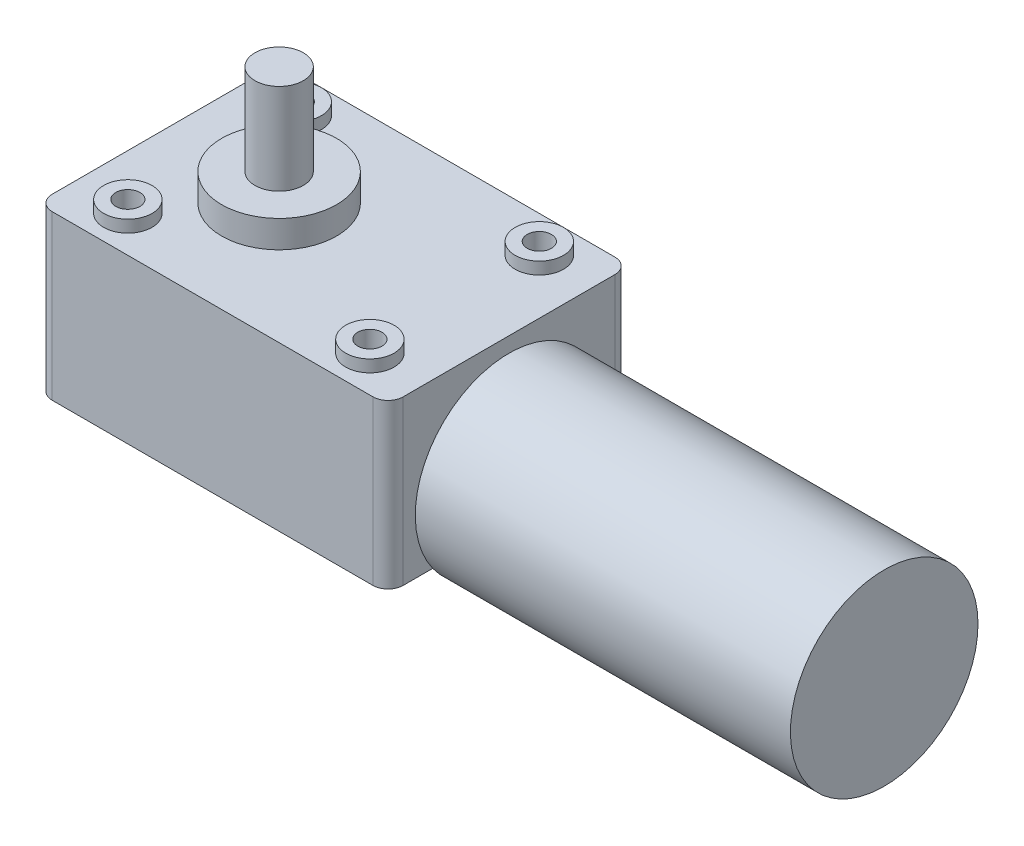
SolidWorks part; units mm, degrees
ref_plane "Front Plane" through (0, 0, 0) normal (0, 0, 1) x (1, 0, 0)
ref_plane "Top Plane" through (0, 0, 0) normal (0, 1, 0) x (1, 0, 0)
ref_plane "Right Plane" through (0, 0, 0) normal (1, 0, 0) x (0, 0, -1)
sketch "Sketch1" plane through (0, 0, 0) normal (0, 1, 0) x (1, 0, 0)
  line L1 (-26.5, -20) -> (26.5, -20)
  line L2 (-29, -17.5) -> (-29, 17.5)
  line L3 (-26.5, 20) -> (26.5, 20)
  line L4 (29, -17.5) -> (29, 17.5)
  line L5 (-29, -20) -> (29, 20) construction
  line L6 (-29, 20) -> (29, -20) construction
  arc A0 (-29, -17.5) -> (-26.5, -20) centre (-26.5, -17.5) ccw
  arc A1 (26.5, -20) -> (29, -17.5) centre (26.5, -17.5) ccw
  arc A2 (29, 17.5) -> (26.5, 20) centre (26.5, 17.5) ccw
  arc A3 (-29, 17.5) -> (-26.5, 20) centre (-26.5, 17.5) cw
  point P0 (0, 0)
  dimension "D3" = 2.5
  dimension "D1" = 58
  dimension "D2" = 40
extrude "Boss-Extrude1" add sketch "Sketch1" along normal mid plane 27
sketch "Sketch2" plane through (0, 13.5, 0) normal (0, 1, 0) x (1, 0, 0)
  line L0 (-1000, 0) -> (49000, 0) construction
  line L1 (-1000.4558, 14) -> (48999.5442, 14) construction
  line L2 (-1000.9116, -14) -> (48999.0884, -14) construction
  line L3 (-20, -994.0746) -> (-20, 49005.9254) construction
  line L4 (20, -995.2141) -> (20, 49004.7859) construction
  line L5 (-29, 17.5) -> (-29, -17.5) construction
  circle A0 centre (-20, 14) radius 4
  circle A1 centre (-20, -14) radius 4
  circle A2 centre (20, -14) radius 4
  circle A3 centre (20, 14) radius 4
  dimension "D5" = 8
  dimension "D6" = 8
  dimension "D7" = 8
  dimension "D8" = 8
  dimension "D1" = 14
  dimension "D2" = 14
  dimension "D3" = 9
  dimension "D4" = 40
extrude "Boss-Extrude2" add sketch "Sketch2" along normal blind 2
sketch "Sketch3" plane through (0, 15.5, 0) normal (0, 1, 0) x (1, 0, 0)
  circle A0 centre (-20, 14) radius 2
  circle A1 centre (20, 14) radius 2
  circle A2 centre (20, -14) radius 2
  circle A3 centre (-20, -14) radius 2
  dimension "D1" = 4
  dimension "D2" = 4
  dimension "D3" = 4
  dimension "D4" = 4
extrude "Cut-Extrude1" cut sketch "Sketch3" against normal blind 6
sketch "Sketch6" plane through (0, 13.5, 0) normal (0, 1, 0) x (1, 0, 0)
  line L0 (-1000, 0) -> (49000, 0) construction
  line L1 (-29, 17.5) -> (-29, -17.5) construction
  circle A0 centre (-9, 0) radius 9.5
  dimension "D1" = 19
  dimension "D2" = 20
extrude "Boss-Extrude5" add sketch "Sketch6" along normal blind 4.5
sketch "Sketch4" plane through (0, 18, 0) normal (0, 1, 0) x (1, 0, 0)
  circle A0 centre (-9, 0) radius 4
  circle A1 centre (-9, 0) radius 9.5 construction
  dimension "D1" = 8
extrude "Boss-Extrude3" add sketch "Sketch4" along normal blind 15
sketch "Sketch5" plane through (29, 0, 0) normal (1, 0, 0) x (0, 0, -1)
  line L0 (-17.5, 13.5) -> (17.5, 13.5) construction
  line L1 (0, -1000) -> (0, 49000) construction
  circle A0 centre (0, -4.5) radius 15.5
  dimension "D2" = 31
  dimension "D3" = 18
extrude "Boss-Extrude4" add sketch "Sketch5" along normal blind 62
mirror "Mirror2" about plane through (0, 0, 0) normal (0, 1, 0) of "Boss-Extrude5", "Cut-Extrude1", "Boss-Extrude2"
sketch "Sketch7" plane through (0, -18, 0) normal (0, -1, 0) x (1, 0, 0)
  circle A0 centre (-9, 0) radius 4
  dimension "D1" = 8
extrude "Cut-Extrude2" cut sketch "Sketch7" against normal blind 1.7
